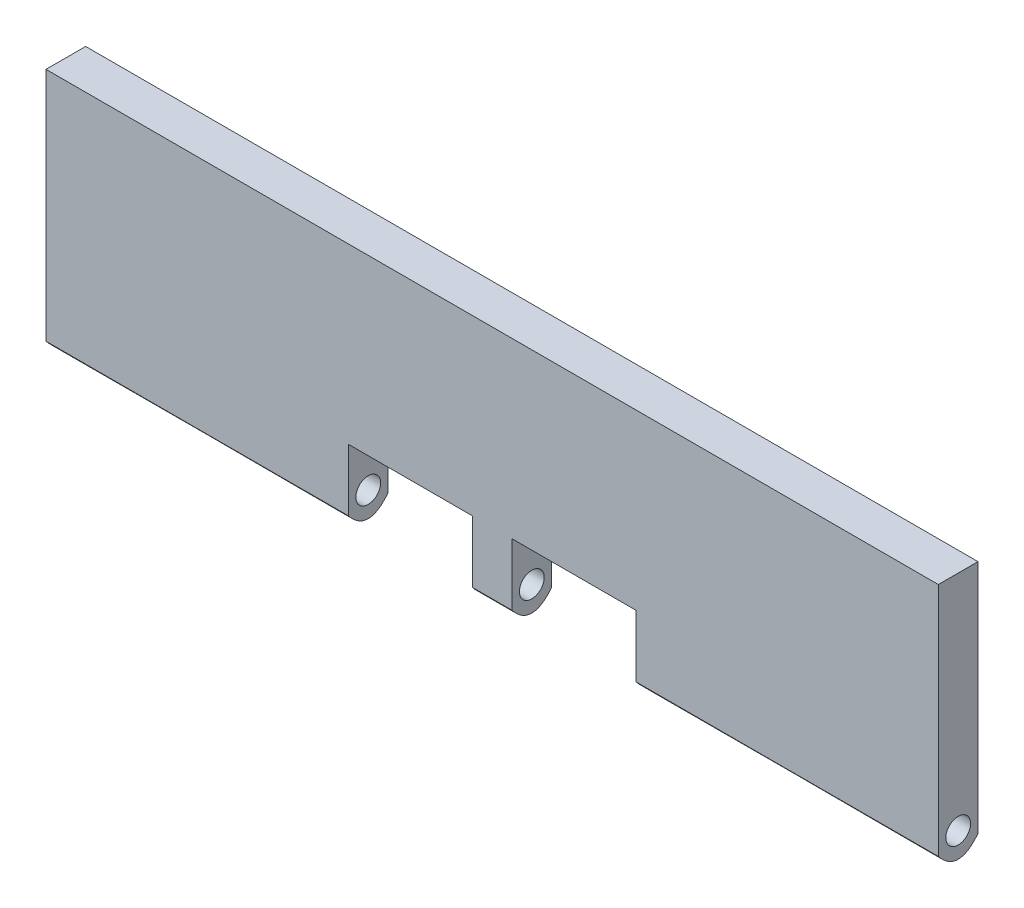
SolidWorks part; units mm, degrees
ref_plane "Plan de face" through (0, 0, 0) normal (0, 0, 1) x (1, 0, 0)
ref_plane "Plan de dessus" through (0, 0, 0) normal (0, 1, 0) x (1, 0, 0)
ref_plane "Plan de droite" through (0, 0, 0) normal (1, 0, 0) x (0, 0, -1)
sketch "Esquisse1" plane through (0, 0, 0) normal (0, 0, 1) x (1, 0, 0)
  line L0 (-29, -25) -> (-29, -10)
  line L1 (-90, -25) -> (-29, -25)
  line L2 (-90, -25) -> (-90, 25)
  line L3 (-90, 25) -> (90, 25)
  line L4 (90, -25) -> (90, 25)
  line L5 (-90, -25) -> (90, 25) construction
  line L6 (-90, 25) -> (90, -25) construction
  line L7 (-29, -10) -> (-4, -10)
  line L8 (-4, -10) -> (-4, -25)
  line L9 (0, 0) -> (0, -25) construction
  line L10 (-4, -25) -> (4, -25)
  line L11 (4, -10) -> (4, -25)
  line L12 (29, -10) -> (4, -10)
  line L13 (29, -25) -> (29, -10)
  line L14 (29, -25) -> (90, -25)
  point P0 (0, 0)
  dimension "D1" = 180
  dimension "D2" = 50
  dimension "D3" = 25
  dimension "D4" = 4
  dimension "D5" = 15
extrude "Boss.-Extru.1" add sketch "Esquisse1" along normal blind 8
sketch "Esquisse2" plane through (-90, 0, 0) normal (-1, 0, 0) x (0, 0, 1)
  line L0 (4, -25) -> (4, -8.5674) construction
  line L1 (8, -25) -> (0, -25) construction
  line L2 (4, -22.5) -> (0, -22.5) construction
  line L3 (0, 25) -> (0, -25) construction
  line L4 (8, 25) -> (8, -25) construction
  line L5 (0, -22.5) -> (0, -25)
  line L6 (0, -25) -> (8, -25)
  line L7 (8, -25) -> (8, -22.5)
  circle A0 centre (4, -20) radius 2.5
  spline S0 degree 2 poles (0, -22.5) (4, -27.5) (8, -22.5) knots 0 0 0 1 1 1
  line M1 (0, 25) -> (0, -25)
  line M2 (0, -25) -> (8, -25)
  line M3 (8, -25) -> (8, 25)
  dimension "D1" = 5
  dimension "D2" = 5
extrude "Enlèv. mat.-Extru.1" cut sketch "Esquisse2" against normal up to surface (180 mm away) contours S0 L6 M3 | S0 M1 M2 | A0 up to face at (90, 0, 4)
sketch "Esquisse4" plane through (0, 0, 0) normal (1, 0, 0) x (0, 0, -1)
  line L0 (0, 0) -> (5, 0) construction
  line L1 (5, 4.5) -> (0, 4.5)
  line L2 (0, 25) -> (0, -22.5) construction
  line L3 (5, -4.5) -> (0, -4.5)
  line L4 (0, 4.5) -> (0, -4.5)
  circle A0 centre (5, 0) radius 2.5
  arc A1 (5, -4.5) -> (5, 4.5) centre (5, 0) ccw
  dimension "D1" = 5
  dimension "D2" = 2
  dimension "D3" = 5
extrude "Boss.-Extru.2" add sketch "Esquisse4" along normal blind 2.5 and the other way blind 2.5
